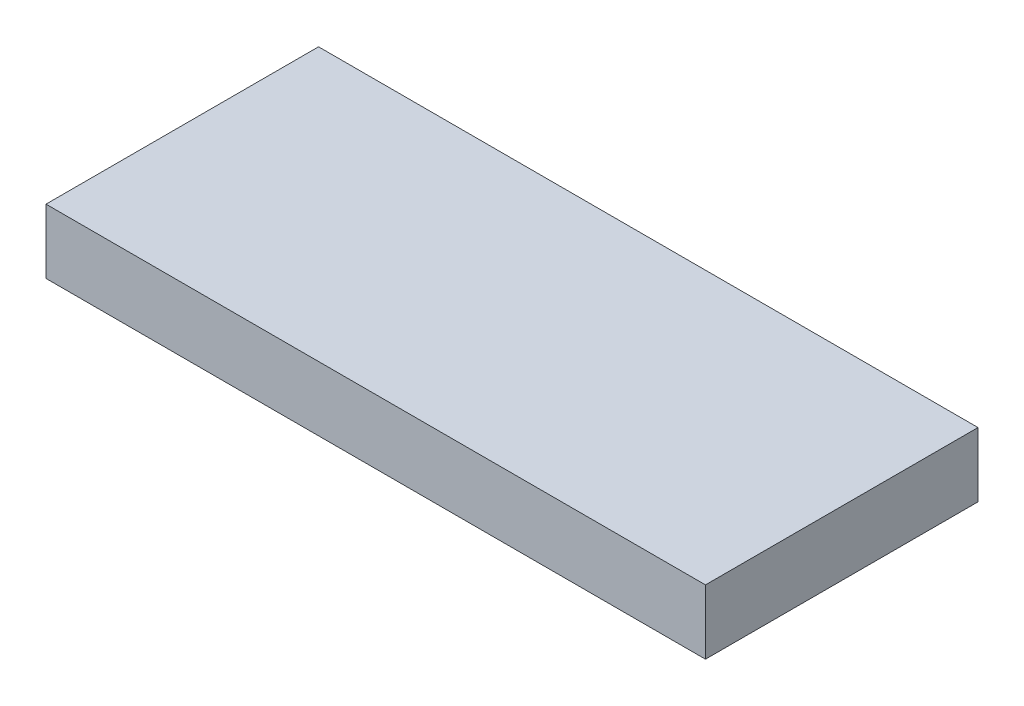
SolidWorks part; units mm, degrees
material "Plain Carbon Steel"
ref_plane "Front Plane" through (0, 0, 0) normal (0, 0, 1) x (1, 0, 0)
ref_plane "Top Plane" through (0, 0, 0) normal (0, 1, 0) x (1, 0, 0)
ref_plane "Right Plane" through (0, 0, 0) normal (1, 0, 0) x (0, 0, -1)
sketch "Sketch1" plane through (0, 0, 0) normal (0, 1, 0) x (1, 0, 0)
  line L1 (15.365, -6.35) -> (-15.365, -6.35)
  line L2 (15.365, -6.35) -> (15.365, 6.35)
  line L3 (15.365, 6.35) -> (-15.365, 6.35)
  line L4 (-15.365, -6.35) -> (-15.365, 6.35)
  line L5 (15.365, -6.35) -> (-15.365, 6.35) construction
  line L6 (15.365, 6.35) -> (-15.365, -6.35) construction
  point P0 (0, 0)
  dimension "D1" = 12.7
  dimension "D2" = 30.73
extrude "Boss-Extrude1" add sketch "Sketch1" along normal blind 3
